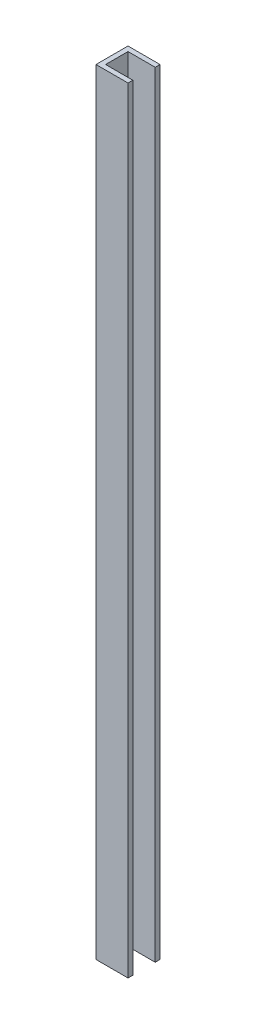
SolidWorks part; units mm, degrees
ref_plane "Front Plane" through (0, 0, 0) normal (0, 0, 1) x (1, 0, 0)
ref_plane "Top Plane" through (0, 0, 0) normal (0, 1, 0) x (1, 0, 0)
ref_plane "Right Plane" through (0, 0, 0) normal (1, 0, 0) x (0, 0, -1)
sketch "Sketch2" plane through (0, 0, 0) normal (0, 1, 0) x (1, 0, 0)
  line L1 (-5, -5) -> (5, -5)
  line L2 (-5, -5) -> (-5, 5)
  line L3 (-5, 5) -> (5, 5)
  line L4 (5, -5) -> (5, 5)
  line L5 (-5, -5) -> (5, 5) construction
  line L6 (-5, 5) -> (5, -5) construction
  line L7 (5, 3.5) -> (-3.5, 3.5)
  line L8 (5, 3.5) -> (5, -3.5)
  line L9 (5, -3.5) -> (-3.5, -3.5)
  line L10 (-3.5, 3.5) -> (-3.5, -3.5)
  point P0 (0, 0)
  point P10 (-13.2045, 8.2727)
  point P11 (0, 0)
  dimension "D1" = 1.5
  dimension "D2" = 1.5
  dimension "D3" = 10
extrude "Boss-Extrude1" add sketch "Sketch2" along normal mid plane 242 contours L10 L7 L4 L3 L2 L1 L9
